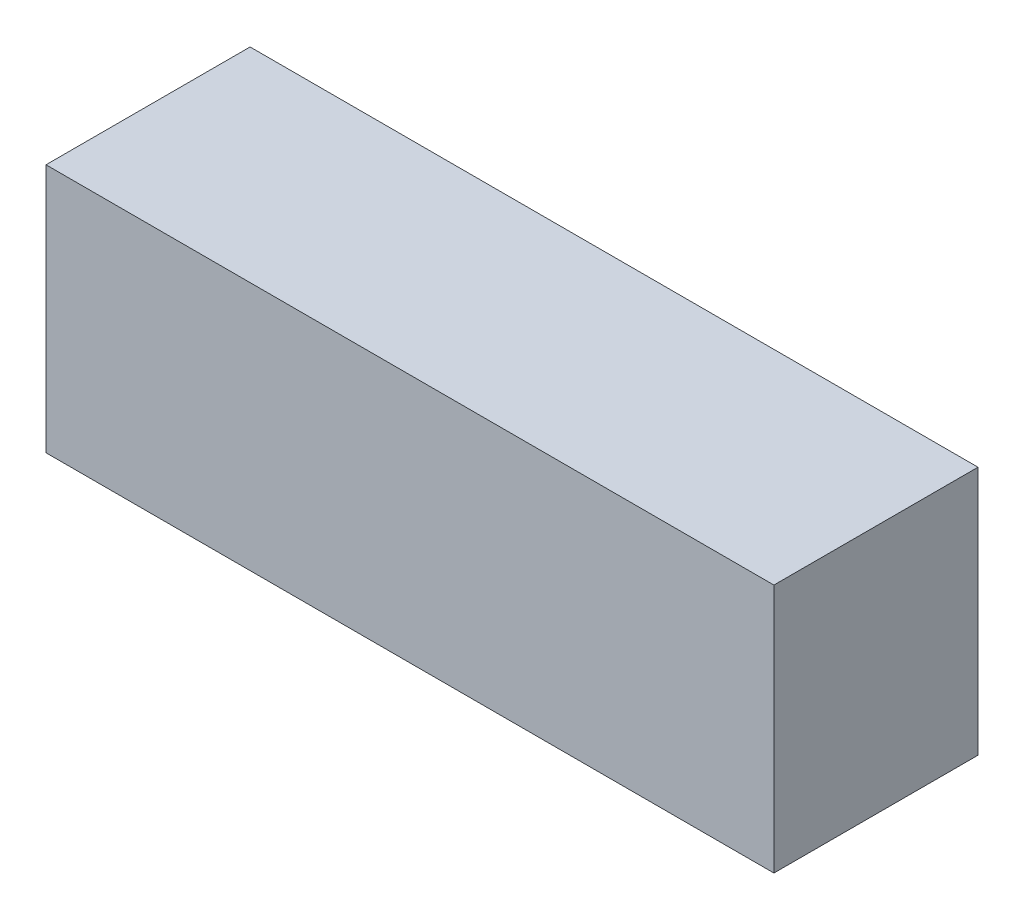
SolidWorks part; units mm, degrees
ref_plane "Front Plane" through (0, 0, 0) normal (0, 0, 1) x (1, 0, 0)
ref_plane "Top Plane" through (0, 0, 0) normal (0, 1, 0) x (1, 0, 0)
ref_plane "Right Plane" through (0, 0, 0) normal (1, 0, 0) x (0, 0, -1)
sketch "Sketch1" plane through (0, 0, 0) normal (0, 0, 1) x (1, 0, 0)
  line L0 (-24.1863, 10.1801) -> (40.0137, 10.1801)
  line L1 (40.0137, 10.1801) -> (40.0137, -11.8199)
  line L2 (40.0137, -11.8199) -> (-24.1863, -11.8199)
  line L3 (-24.1863, -11.8199) -> (-24.1863, 10.1801)
  dimension "D1" = 22
  dimension "D2" = 64.2
extrude "Boss-Extrude1" add sketch "Sketch1" along normal blind 18
